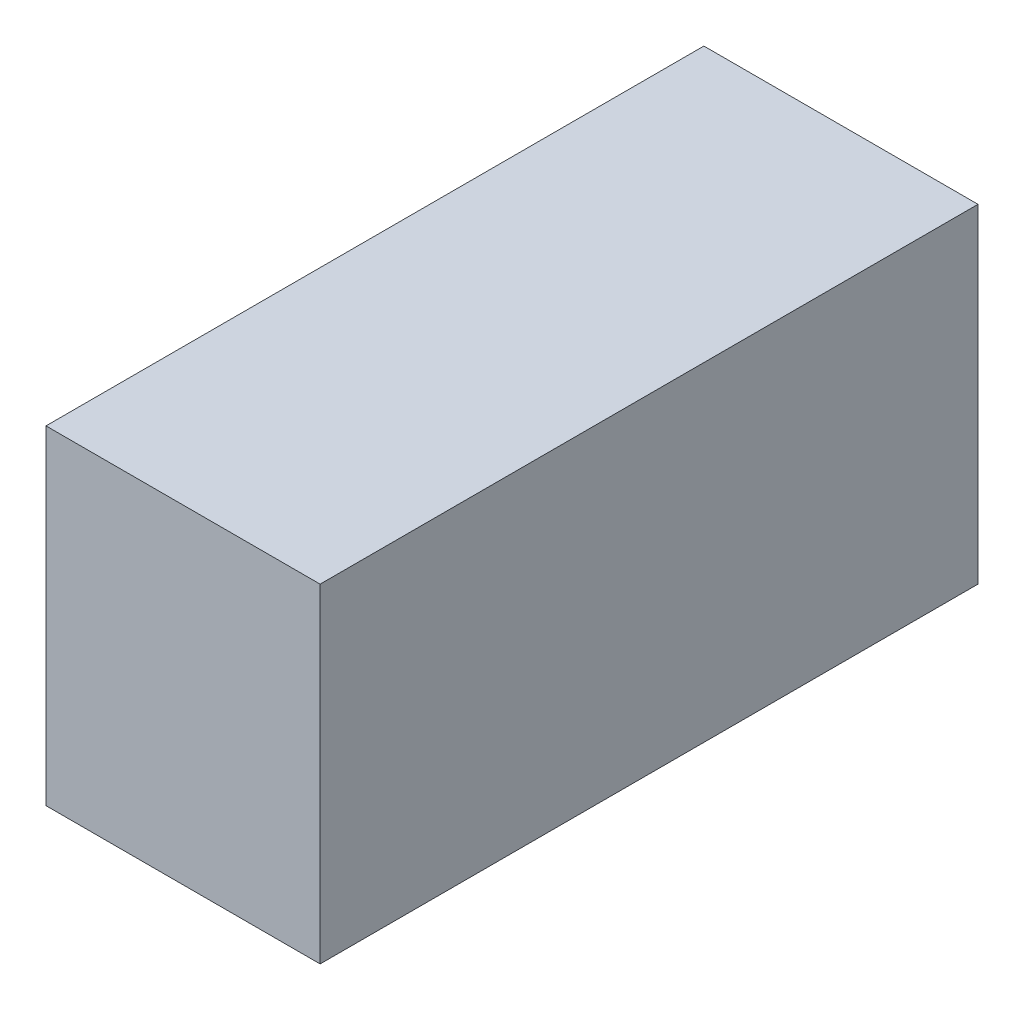
SolidWorks part; units mm, degrees
other "Payload"
ref_plane "Front Plane" through (0, 0, 0) normal (0, 0, 1) x (1, 0, 0)
ref_plane "Top Plane" through (0, 0, 0) normal (0, 1, 0) x (1, 0, 0)
ref_plane "Right Plane" through (0, 0, 0) normal (1, 0, 0) x (0, 0, -1)
sketch "Sketch1" plane through (0, 0, 0) normal (1, 0, 0) x (0, 0, -1)
  line L1 (0, 0) -> (300, 0)
  line L2 (0, 0) -> (0, 150)
  line L3 (0, 150) -> (300, 150)
  line L4 (300, 0) -> (300, 150)
  dimension "D1" = 300
  dimension "D2" = 150
extrude "Boss-Extrude1" add sketch "Sketch1" along normal blind 125
